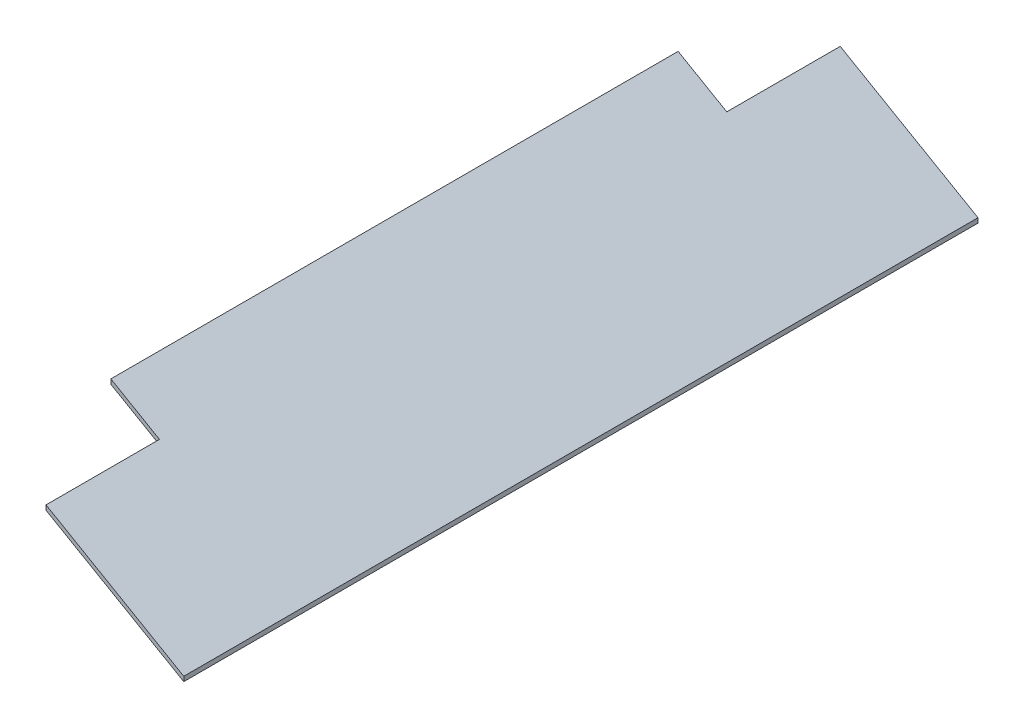
SolidWorks part; units mm, degrees
material "Corrugated Paper"
ref_plane "Front Plane" through (0, 0, 0) normal (0, 0, 1) x (1, 0, 0)
ref_plane "Top Plane" through (0, 0, 0) normal (0, 1, 0) x (1, 0, 0)
ref_plane "Right Plane" through (0, 0, 0) normal (1, 0, 0) x (0, 0, -1)
sketch "Sketch1" plane through (0, 0, 0) normal (0, 0, 1) x (1, 0, 0)
  line L0 (0, 0) -> (0, -3.6662)
  line L1 (0, -3.6662) -> (-146.05, 80.6558)
  line L2 (-146.05, 80.6558) -> (-146.05, 84.322)
  line L3 (-146.05, 84.322) -> (0, 0)
  dimension "D1" = 60
  dimension "D2" = 3.175
  dimension "D3" = 146.05
extrude "Boss-Extrude1" add sketch "Sketch1" along normal mid plane 622.3
sketch "Sketch2" plane through (0, 0, 0) normal (0, 1, 0) x (1, 0, 0)
  line L1 (-146.05, -311.15) -> (-107.95, -311.15)
  line L2 (-146.05, -311.15) -> (-146.05, -222.25)
  line L3 (-146.05, -222.25) -> (-107.95, -222.25)
  line L4 (-107.95, -311.15) -> (-107.95, -222.25)
  line L5 (-146.05, 311.15) -> (-107.95, 311.15)
  line L6 (-146.05, 311.15) -> (-146.05, 222.25)
  line L7 (-146.05, 222.25) -> (-107.95, 222.25)
  line L8 (-107.95, 311.15) -> (-107.95, 222.25)
  dimension "D1" = 88.9
  dimension "D2" = 38.1
extrude "Cut-Extrude1" cut sketch "Sketch2" along normal through all
